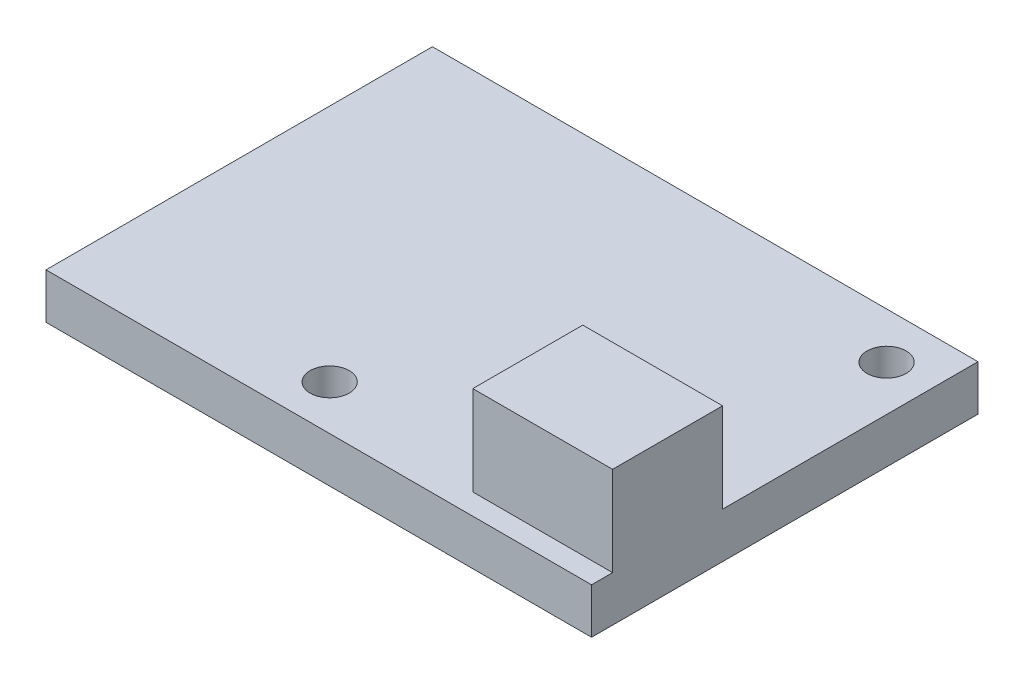
SolidWorks part; units mm, degrees
ref_plane "Front Plane" through (0, 0, 0) normal (0, 0, 1) x (1, 0, 0)
ref_plane "Top Plane" through (0, 0, 0) normal (0, 1, 0) x (1, 0, 0)
ref_plane "Right Plane" through (0, 0, 0) normal (1, 0, 0) x (0, 0, -1)
sketch "Sketch1" plane through (0, 0, 0) normal (0, 1, 0) x (1, 0, 0)
  line L1 (0, 0) -> (30.48, 0)
  line L2 (0, 0) -> (0, 21.59)
  line L3 (0, 21.59) -> (30.48, 21.59)
  line L4 (30.48, 0) -> (30.48, 21.59)
  dimension "D1" = 30.48
  dimension "D2" = 21.59
extrude "Boss-Extrude1" add sketch "Sketch1" along normal blind 2.54
sketch "Sketch2" plane through (0, 2.54, 0) normal (0, 1, 0) x (1, 0, 0)
  line L1 (13.3455, 19.0122) -> (27.9505, 19.0122) construction
  line L2 (13.3455, 19.0122) -> (13.3455, 2.5022) construction
  line L3 (13.3455, 2.5022) -> (27.9505, 2.5022) construction
  line L4 (27.9505, 19.0122) -> (27.9505, 2.5022) construction
  circle A0 centre (27.9505, 19.0122) radius 1.0922
  circle A1 centre (13.3455, 2.5022) radius 1.0922
  dimension "D1" = 2.1844
  dimension "D2" = 14.605
  dimension "D3" = 16.51
  dimension "D4" = 2.1844
extrude "Cut-Extrude1" cut sketch "Sketch2" against normal through all
sketch "Sketch4" plane through (0, 2.54, 0) normal (0, 1, 0) x (1, 0, 0)
  line L0 (30.48, 0) -> (30.48, 21.59) construction
  line L1 (30.48, 7.3198) -> (22.669, 7.3198)
  line L2 (30.48, 7.3198) -> (30.48, 1.1756)
  line L3 (30.48, 1.1756) -> (22.669, 1.1756)
  line L4 (22.669, 7.3198) -> (22.669, 1.1756)
extrude "Boss-Extrude2" add sketch "Sketch4" along normal blind 5
